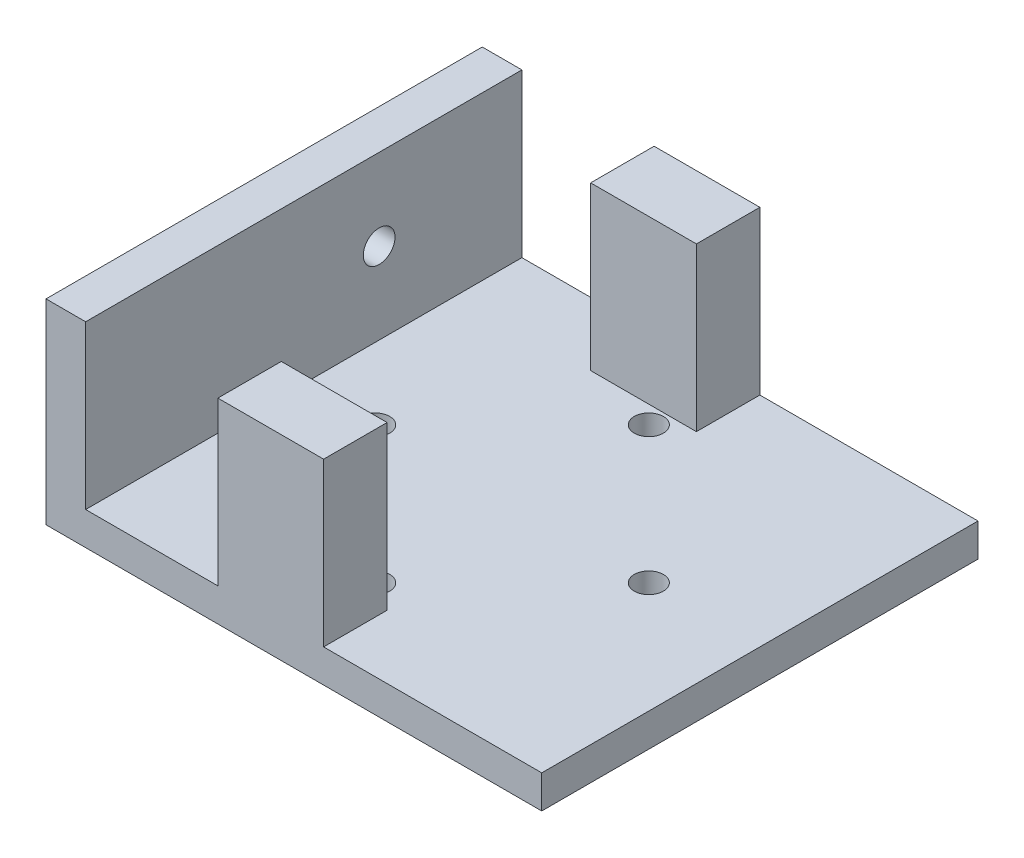
SolidWorks part; units mm, degrees
ref_plane "Ebene vorne" through (0, 0, 0) normal (0, 0, 1) x (1, 0, 0)
ref_plane "Ebene oben" through (0, 0, 0) normal (0, 1, 0) x (1, 0, 0)
ref_plane "Ebene rechts" through (0, 0, 0) normal (1, 0, 0) x (0, 0, -1)
sketch "Skizze1" plane through (0, 0, 0) normal (0, 1, 0) x (1, 0, 0)
  line L1 (-18.75, -16.5) -> (18.75, -16.5)
  line L2 (-18.75, -16.5) -> (-18.75, 16.5)
  line L3 (-18.75, 16.5) -> (18.75, 16.5)
  line L4 (18.75, -16.5) -> (18.75, 16.5)
  line L5 (-18.75, -16.5) -> (18.75, 16.5) construction
  line L6 (-18.75, 16.5) -> (18.75, -16.5) construction
  point P0 (0, 0)
  dimension "D1" = 37.5
  dimension "D2" = 33
extrude "Aufsatz-Linear austragen1" add sketch "Skizze1" along normal blind 2.5
sketch "Skizze2" plane through (0, 2.5, 0) normal (0, 1, 0) x (1, 0, 0)
  line L0 (-18.75, -16.5) -> (18.75, -16.5) construction
  line L1 (-18.75, 16.5) -> (-15.75, 16.5)
  line L2 (-18.75, 16.5) -> (-18.75, -16.5)
  line L3 (-18.75, -16.5) -> (-15.75, -16.5)
  line L4 (-15.75, 16.5) -> (-15.75, -16.5)
  line L5 (18.75, 16.5) -> (-18.75, 16.5) construction
  line L6 (2.25, -16.5) -> (-5.75, -16.5)
  line L7 (2.25, -16.5) -> (2.25, -11.7)
  line L8 (2.25, -11.7) -> (-5.75, -11.7)
  line L9 (-5.75, -16.5) -> (-5.75, -11.7)
  line L10 (2.25, 16.5) -> (-5.75, 16.5)
  line L11 (2.25, 16.5) -> (2.25, 11.7)
  line L12 (2.25, 11.7) -> (-5.75, 11.7)
  line L13 (-5.75, 16.5) -> (-5.75, 11.7)
  dimension "D1" = 3
  dimension "D2" = 18
  dimension "D3" = 8
  dimension "D4" = 8
  dimension "D5" = 18
  dimension "D6" = 4.8
  dimension "D7" = 4.8
extrude "Aufsatz-Linear austragen2" add sketch "Skizze2" along normal blind 12.3
sketch "Skizze3" plane through (0, 14.8, 0) normal (0, 1, 0) x (1, 0, 0)
  line L1 (-15.75, 16.5) -> (-18.75, 16.5)
  line L2 (-15.75, 16.5) -> (-15.75, -16.5)
  line L3 (-15.75, -16.5) -> (-18.75, -16.5)
  line L4 (-18.75, 16.5) -> (-18.75, -16.5)
sketch "Skizze5" plane through (-15.75, 0, 0) normal (1, 0, 0) x (0, 0, -1)
  line L2 (16.5, 14.8) -> (-16.5, 14.8) construction
  line L4 (16.5, 14.8) -> (16.5, 2.5) construction
  circle A1 centre (5.7, 8.65) radius 1.2
  dimension "D2" = 6.15
  dimension "D1" = 2.4
  dimension "D3" = 10.8
sketch "Skizze6" plane through (0, 0, 0) normal (0, -1, 0) x (1, 0, 0)
  arc A0 (1.0984, 10.2915) -> (-1.0984, 10.2915) centre (0, 0) ccw
  circle A1 centre (-10.35, 0) radius 1.1
  circle A2 centre (0, 10.35) radius 1.1
  circle A3 centre (10.35, 0) radius 1.1
  circle A4 centre (0, -10.35) radius 1.1
  arc A5 (10.2915, -1.0984) -> (10.2915, 1.0984) centre (0, 0) ccw
  arc A6 (-1.0984, -10.2915) -> (1.0984, -10.2915) centre (0, 0) ccw
  arc A7 (-10.2915, 1.0984) -> (-10.2915, -1.0984) centre (0, 0) ccw
  dimension "D1" = 20.7
  dimension "D2" = 2.2
  dimension "D3" = 2.2
  dimension "D4" = 2.2
  dimension "D5" = 2.2
extrude "Schnitt-Linear austragen3" cut sketch "Skizze6" against normal through all contours A7 A1 | A1 A7 | A0 A2 | A0 A2 | A3 A5 | A5 A3 | A4 A6 | A6 A4
extrude "Schnitt-Linear austragen4" cut sketch "Skizze5" against normal through all
